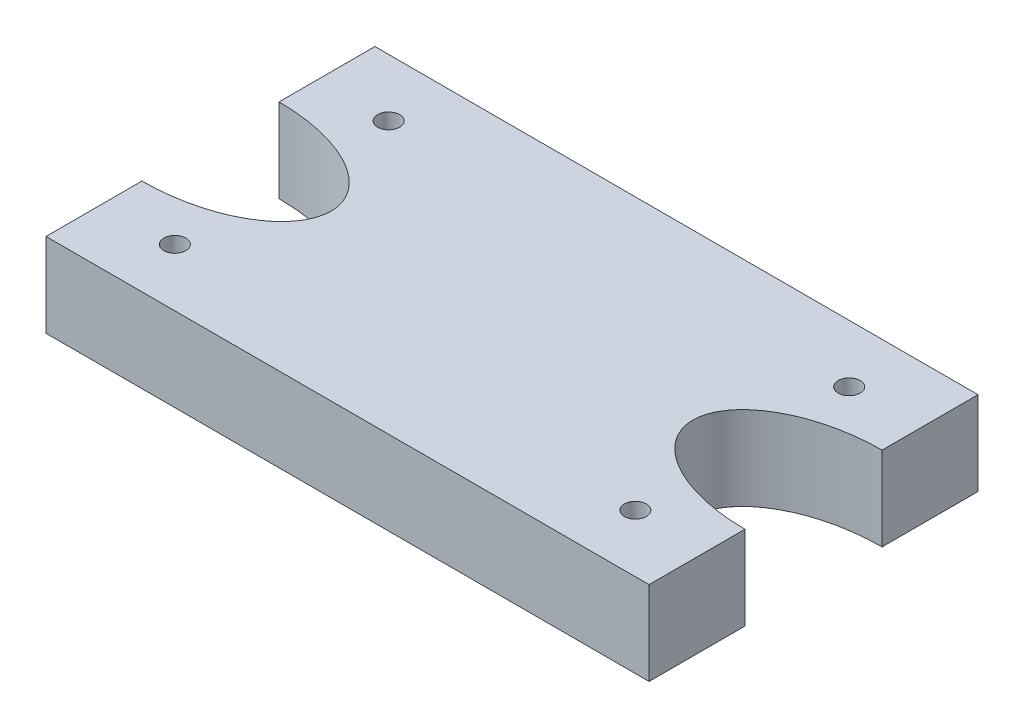
SolidWorks part; units mm, degrees
material "Balsa"
ref_plane "Plan de face" through (0, 0, 0) normal (0, 0, 1) x (1, 0, 0)
ref_plane "Plan de dessus" through (0, 0, 0) normal (0, 1, 0) x (1, 0, 0)
ref_plane "Plan de droite" through (0, 0, 0) normal (1, 0, 0) x (0, 0, -1)
sketch "Esquisse1" plane through (0, 0, 0) normal (0, 1, 0) x (1, 0, 0)
  line L1 (-35.268, 18.9703) -> (74.732, 18.9703)
  line L2 (-35.268, 18.9703) -> (-35.268, -41.0297)
  line L3 (-35.268, -41.0297) -> (74.732, -41.0297)
  line L4 (74.732, 18.9703) -> (74.732, -41.0297)
  dimension "D1" = 110
  dimension "D2" = 60
extrude "Boss.-Extru.1" add sketch "Esquisse1" along normal blind 15.3
sketch "Esquisse2" plane through (0, 15.3, 0) normal (0, 1, 0) x (1, 0, 0)
  line L2 (-35.268, 18.9703) -> (-35.268, -41.0297) construction
  line L3 (74.732, -41.0297) -> (74.732, 18.9703) construction
  line L5 (74.732, 18.9703) -> (-35.268, 18.9703) construction
  line L6 (-35.268, -41.0297) -> (74.732, -41.0297) construction
  circle A0 centre (61.732, 8.4703) radius 2
  circle A1 centre (61.732, -30.5297) radius 2
  circle A2 centre (-22.268, 8.4703) radius 2
  circle A3 centre (-22.268, -30.5297) radius 2
  dimension "D1" = 4
  dimension "D2" = 4
  dimension "D6" = 4
  dimension "D7" = 4
  dimension "D3" = 39
  dimension "D4" = 10.5
  dimension "D5" = 10.5
  dimension "D8" = 10.5
  dimension "D9" = 39
  dimension "D10" = 84
  dimension "D11" = 13
  dimension "D12" = 13
  dimension "D13" = 84
extrude "Enlèv. mat.-Extru.2" cut sketch "Esquisse2" against normal through all
sketch "Esquisse5" plane through (0, 15.3, 0) normal (0, 1, 0) x (1, 0, 0)
  line L0 (-35.268, 18.9703) -> (-35.268, -41.0297) construction
  line L1 (74.732, -41.0297) -> (74.732, 18.9703) construction
  ellipse E0 centre (-35.268, -11.0297) end of major axis (-13.268, -11.0297) minor radius 12.5
  ellipse E1 centre (74.732, -11.0297) end of major axis (52.732, -11.0297) minor radius 12.5
  dimension "D1" = 44
  dimension "D2" = 25
  dimension "D3" = 25
  dimension "D4" = 44
extrude "Enlèv. mat.-Extru.4" cut sketch "Esquisse5" against normal through all
